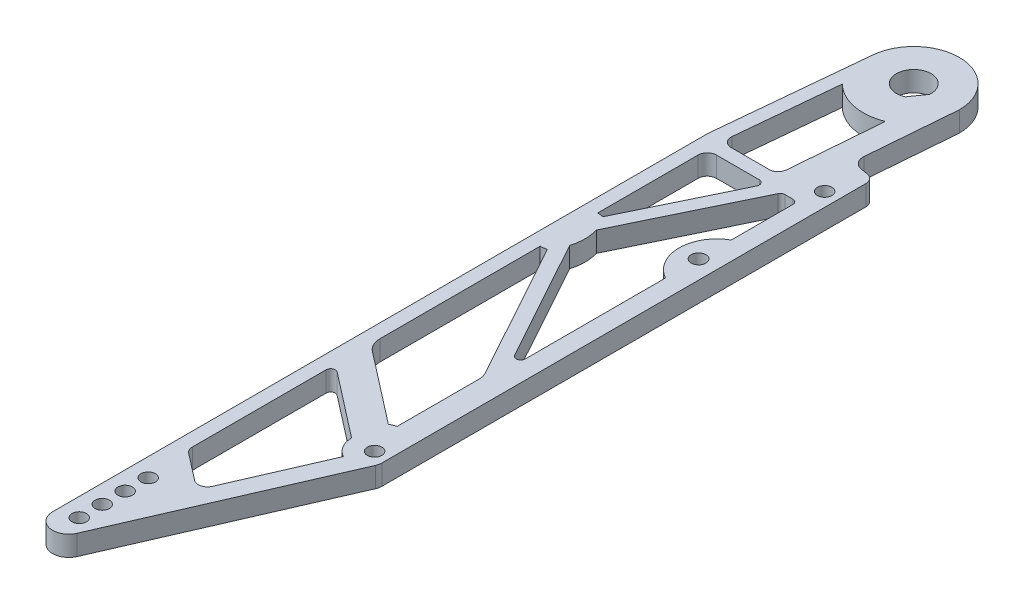
SolidWorks part; units mm, degrees
material "6061-T6 (SS)"
ref_plane "X-Y Datum" through (0, 0, 0) normal (0, 0, 1) x (1, 0, 0)
ref_plane "X-Z Datum" through (0, 0, 0) normal (0, 1, 0) x (1, 0, 0)
ref_plane "Y-Z Datum" through (0, 0, 0) normal (1, 0, 0) x (0, 0, -1)
other "Graphic1" [suppressed]
other "Graphic (Closed) -1" [suppressed]
sketch "Sketch2" plane through (0, 0, 0) normal (0, 1, 0) x (1, 0, 0)
  line L5 (13.4859, -162.4108) -> (-11.43, -143.082) construction
  line L8 (0, 0) -> (0, -24.13) construction
  line L11 (15.1556, -28.0184) -> (13.2387, -27.713)
  line L15 (-16.51, -221.3289) -> (-16.51, -40.4661)
  line L22 (-7.9887, -223.1013) -> (16.9799, -165.6775)
  line L23 (17.2959, -164.1583) -> (17.2959, -30.5268)
  line L33 (10.4385, -167.9818) -> (-0.5342, -193.2173)
  line L44 (-8.8047, -78.8772) -> (7.5755, -45.0536)
  line L45 (8.7185, -44.3372) -> (10.9459, -44.3372)
  line L47 (9.8331, -120.1049) -> (-8.8047, -86.2228)
  line L49 (-12.4315, -37.7433) -> (-9.7554, -9.9996)
  line L51 (5.1277, -12.9949) -> (3.0693, -38.194)
  line L53 (0.5377, -40.5272) -> (-9.9032, -40.5272)
  line L56 (1.663, -44.3372) -> (-10.16, -44.3372)
  line L57 (13.7382, -24.5776) -> (0, 0) construction
  line L58 (10.5738, -24.3191) -> (12.5603, 0)
  line L59 (-12.7, -149.6154) -> (-12.7, -186.5441)
  line L63 (7.1359, -162.4108) -> (-10.6516, -148.612)
  line L64 (-12.7, -74.6125) -> (-12.7, -46.8772)
  line L65 (2.8061, -46.1607) -> (-11.056, -74.7846)
  line L66 (-16.4983, -40.2222) -> (-12.5023, 1.2059)
  line L67 (-4.4204, -194.2114) -> (-11.7169, -188.551)
  line L68 (5.8058, -44.3372) -> (-12.7, -82.55) construction
  line L69 (-1.7326, -64.2739) -> (-5.1616, -62.6133) construction
  line L70 (8.9236, -154.0495) -> (-10.7338, -138.8001)
  line L71 (10.6561, -153.3158) -> (10.6561, -130.811)
  line L72 (10.0271, -128.3626) -> (-10.9185, -90.285)
  line L75 (-12.7, -134.7862) -> (-12.7, -90.4875)
  line L76 (4.757, -0.4162) -> (2.0181, -4.3278)
  line L77 (3.3876, -2.372) -> (0, 0) construction
  line L78 (12.2159, -45.6072) -> (12.2159, -62.6181)
  line L79 (12.2159, -80.8) -> (12.2159, -119.4928)
  line L80 (0, 0) -> (-4.7752, 0) construction
  circle A0 centre (0, 0) radius 4.7752
  circle A2 centre (-11.43, -219.075) radius 2
  circle A3 centre (-11.43, -212.725) radius 2
  circle A4 centre (-11.43, -206.375) radius 2
  circle A5 centre (-11.43, -200.025) radius 2
  circle A7 centre (0, 0) radius 12.5603 construction
  circle A12 centre (13.4859, -38.1) radius 2
  arc A13 (-12.5023, 1.2059) -> (12.5603, 0) centre (0, 0) cw
  arc A14 (-8.8047, -86.2228) -> (-8.8047, -78.8772) centre (-20.962, -82.55) ccw
  circle A16 centre (24.0125, -14.7036) radius 3.175 construction
  arc A17 (24.0125, -14.7036) -> (13.7382, -24.5776) centre (0, 0) cw construction
  circle A18 centre (13.7382, -24.5776) radius 3.175 construction
  arc A19 (13.2387, -27.713) -> (10.5738, -24.3191) centre (13.7382, -24.5776) cw
  arc A20 (15.1556, -28.0184) -> (17.2959, -30.5268) centre (14.7559, -30.5268) cw
  circle A21 centre (13.4859, -162.4108) radius 2
  arc A24 (10.4385, -167.9818) -> (7.1359, -162.4108) centre (13.4859, -162.4108) cw
  arc A25 (-16.51, -221.3289) -> (-7.9887, -223.1013) centre (-12.065, -221.3289) ccw
  arc A26 (-12.7, -74.6125) -> (-11.056, -74.7846) centre (-12.7, -82.55) cw
  arc A28 (5.1277, -12.9949) -> (-9.7554, -9.9996) centre (0, 0) cw
  arc A31 (-10.16, -44.3372) -> (-12.7, -46.8772) centre (-10.16, -46.8772) ccw
  arc A32 (-12.4315, -37.7433) -> (-9.9032, -40.5272) centre (-9.9032, -37.9872) ccw
  arc A33 (0.5377, -40.5272) -> (3.0693, -38.194) centre (0.5377, -37.9872) ccw
  arc A36 (-12.7, -149.6154) -> (-10.6516, -148.612) centre (-11.43, -149.6154) cw
  arc A37 (9.8331, -120.1049) -> (12.2159, -119.4928) centre (10.9459, -119.4928) ccw
  arc A38 (7.5755, -45.0536) -> (8.7185, -44.3372) centre (8.7185, -45.6072) cw
  arc A39 (10.9459, -44.3372) -> (12.2159, -45.6072) centre (10.9459, -45.6072) cw
  arc A40 (1.663, -44.3372) -> (2.8061, -46.1607) centre (1.663, -45.6072) cw
  arc A50 (17.2959, -164.1583) -> (16.9799, -165.6775) centre (13.4859, -164.1583) cw
  arc A52 (-16.4983, -40.2222) -> (-16.51, -40.4661) centre (-13.97, -40.4661) ccw
  arc A53 (-12.7, -186.5441) -> (-11.7169, -188.551) centre (-10.16, -186.5441) ccw
  arc A54 (-4.4204, -194.2114) -> (-0.5342, -193.2173) centre (-2.8635, -192.2045) ccw
  arc A55 (10.6561, -153.3158) -> (8.9236, -154.0495) centre (13.4859, -162.4108) ccw
  arc A56 (-10.9185, -90.285) -> (-12.7, -90.4875) centre (-12.7, -82.55) cw
  arc A57 (-12.7, -134.7862) -> (-10.7338, -138.8001) centre (-7.62, -134.7862) ccw
  arc A58 (10.0271, -128.3626) -> (10.6561, -130.811) centre (5.5761, -130.811) cw
  arc A59 (12.2159, -62.6181) -> (12.2159, -80.8) centre (17.2959, -71.7091) ccw
  circle A60 centre (12.2159, -71.7091) radius 2.032
  point P30 (17.2959, -28.3595)
  point P44 (-3.4471, -63.4436)
  point P45 (-1.8376, -196.215)
  point P75 (-4.7752, 0)
  point P88 (-12.7, -44.3372)
  point P91 (-12.7, -40.5272)
  point P104 (10.6561, -121.6534)
  point P107 (7.9224, -44.3372)
  point P110 (12.2159, -44.3372)
  point P120 (17.2959, -164.9508)
  dimension "D1" = 9.5504
  dimension "D6" = 4
  dimension "D12" = 24.13
  dimension "D5" = 25.1206
  dimension "D14" = 5.08
  dimension "D19" = 4
  dimension "D20" = 6.35
  dimension "D24" = 3.81
  dimension "D50" = 12.7
  dimension "D51" = 8.262
  dimension "D42" = 3.81
  dimension "D62" = 6.35
  dimension "D63" = 29.204
  dimension "D27" = 2.54
  dimension "D44" = 4
  dimension "D18" = 4.445
  dimension "D34" = 3.81
  dimension "D36" = 6.35
  dimension "D33" = 13.97
  dimension "D38" = 3.81
  dimension "D39" = 8.89
  dimension "D48" = 2.54
  dimension "D49" = 1.27
  dimension "D52" = 3.81
  dimension "D53" = 3.81
  dimension "D54" = 9.525
  dimension "D58" = 2.54
  dimension "D59" = 3.81
  dimension "D64" = 4.7752
  dimension "D65" = 10.414
  dimension "D29" = 7.9375
  dimension "D31" = 3.81
  dimension "D41" = 2.54
  dimension "D55" = 7.9375
  dimension "D57" = 5.08
  dimension "D66" = 10.8409
  dimension "D25" = 4.064
  dimension "D7" = 6.35
  dimension "D8" = 6.35
  dimension "D9" = 6.35
  dimension "D10" = 5.08
  dimension "D11" = 5.08
  dimension "D13" = 4.1084
  dimension "D15" = 82.55
  dimension "D16" = 12.7
  dimension "D17" = 13.7382
  dimension "D21" = 136.5913
  dimension "D22" = 38.1
  dimension "D23" = 13.4859
  dimension "D26" = 3.81
  dimension "D28" = 40.5272
  dimension "D30" = 2.54
  dimension "D32" = 3.81
  dimension "D35" = 3.81
  dimension "D37" = 16.51
  dimension "D40" = 23.5
  dimension "D43" = 200.025
  dimension "D45" = 6.35
  dimension "D46" = 6.35
  dimension "D47" = 4.2935
  dimension "D56" = 3.81
  dimension "D60" = 24.0125
  dimension "D61" = 14.7036
  dimension "D67" = 5.08
  dimension "D68" = 55
extrude "Boss-Extrude1" add sketch "Sketch2" along normal blind 5.588 contours L76 A0
sketch "Sketch6" plane through (-16.51, 0, 0) normal (-1, 0, 0) x (0, 0, 1)
  line L0 (183.2289, 5.588) -> (183.2289, 0)
  line L1 (221.3289, 0) -> (40.4661, 0) construction
  line L2 (221.3289, 5.588) -> (40.4661, 5.588) construction
  line L3 (221.3289, 5.588) -> (221.3289, 0) construction
  dimension "D1" = 38.1
split line "Split Line2"
sketch "Sketch7" plane through (0, 5.588, 0) normal (0, 1, 0) x (1, 0, 0)
  line L0 (17.2959, -164.1583) -> (17.2959, -30.5268) construction
  circle A0 centre (12.2159, -71.656) radius 2.032
  dimension "D3" = 4.064
  dimension "D1" = 5.08
  dimension "D2" = 9.144
extrude "Cut-Extrude1" cut sketch "Sketch7" against normal up to surface (5.588 mm away) up to face at (-0.889, 0, 127.6367)
